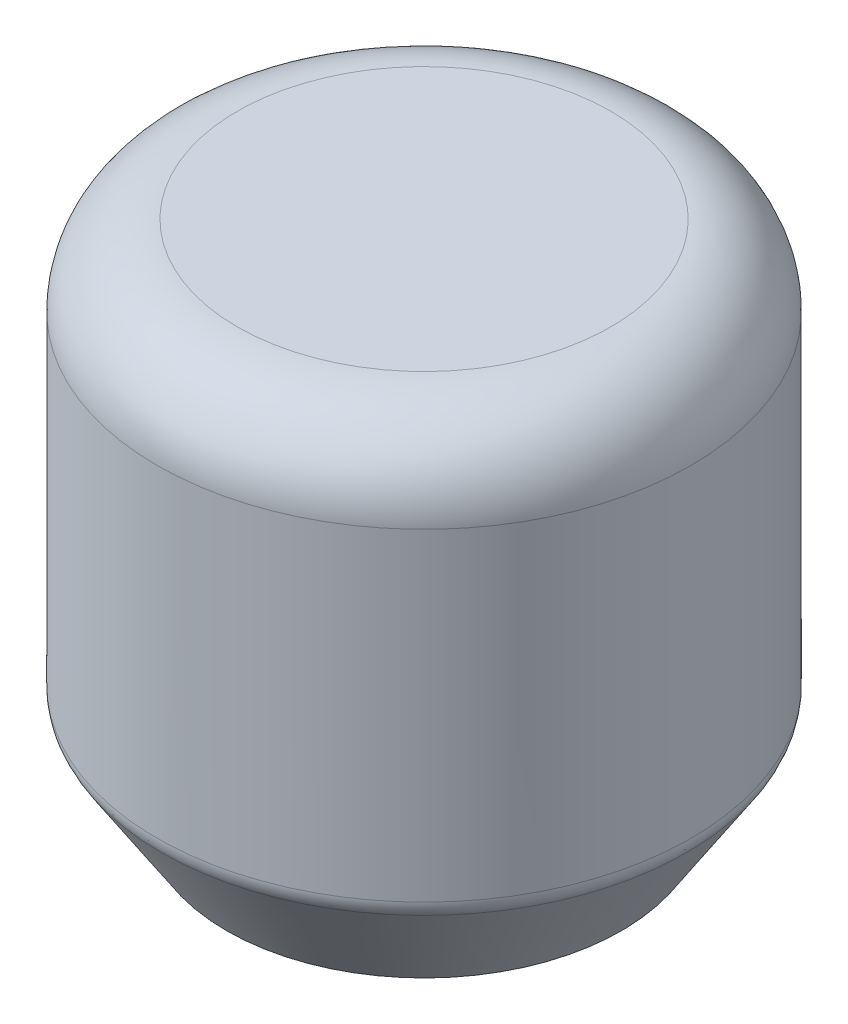
SolidWorks part; units mm, degrees
ref_plane "Front Plane" through (0, 0, 0) normal (0, 0, 1) x (1, 0, 0)
ref_plane "Top Plane" through (0, 0, 0) normal (0, 1, 0) x (1, 0, 0)
ref_plane "Right Plane" through (0, 0, 0) normal (1, 0, 0) x (0, 0, -1)
sketch "Sketch1" plane through (0, 0, 0) normal (0, 1, 0) x (1, 0, 0)
  circle A1 centre (0, 0) radius 127
extrude "Boss-Extrude1" add sketch "Sketch1" along normal blind 246.38 contours A1
fillet "Fillet1" radius 38.1 1 edges at (0, 246.38, 127)
chamfer "Chamfer1" distance 33.02 angle 57 1 edges at (0, 0, 127)
fillet "Fillet2" radius 12.7 1 edges at (0, 50.8463, 127)
